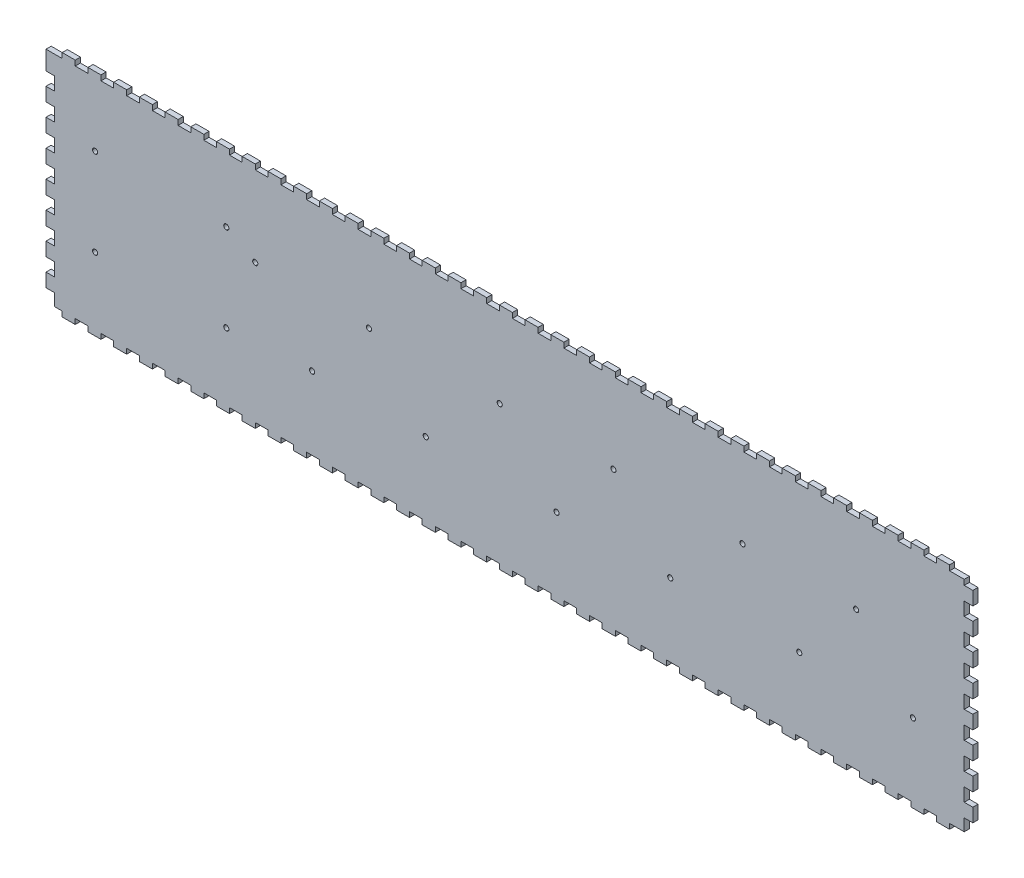
SolidWorks part; units mm, degrees
material "Perspex (TM) GS Acrylic Cast Sheet"
ref_plane "Front Plane" through (0, 0, 0) normal (0, 0, 1) x (1, 0, 0)
ref_plane "Top Plane" through (0, 0, 0) normal (0, 1, 0) x (1, 0, 0)
ref_plane "Right Plane" through (0, 0, 0) normal (1, 0, 0) x (0, 0, -1)
sketch "Sketch1" plane through (0, 0, 0) normal (0, 0, 1) x (1, 0, 0)
  line L0 (533.3602, 7.7159) -> (533.3602, 0.71)
  line L1 (9.4185, 0.71) -> (9.4185, -2.29)
  line L2 (9.4185, -2.29) -> (16.9869, -2.29)
  line L3 (16.9869, 0.71) -> (16.9869, -2.29)
  line L4 (16.9869, 0.71) -> (24.3553, 0.71)
  line L5 (24.3553, 0.71) -> (24.3553, -2.29)
  line L6 (24.3553, -2.29) -> (31.9238, -2.29)
  line L7 (31.9238, 0.71) -> (31.9238, -2.29)
  line L8 (31.9238, 0.71) -> (39.2923, 0.71)
  line L9 (39.2923, 0.71) -> (39.2923, -2.29)
  line L10 (39.2923, -2.29) -> (46.8607, -2.29)
  line L11 (46.8607, 0.71) -> (46.8607, -2.29)
  line L12 (46.8607, 0.71) -> (54.2292, 0.71)
  line L13 (54.2292, 0.71) -> (54.2292, -2.29)
  line L14 (54.2292, -2.29) -> (61.7976, -2.29)
  line L15 (61.7976, 0.71) -> (61.7976, -2.29)
  line L16 (61.7976, 0.71) -> (69.1661, 0.71)
  line L17 (69.1661, 0.71) -> (69.1661, -2.29)
  line L18 (69.1661, -2.29) -> (76.7345, -2.29)
  line L19 (76.7345, 0.71) -> (76.7345, -2.29)
  line L20 (76.7345, 0.71) -> (84.103, 0.71)
  line L21 (84.103, 0.71) -> (84.103, -2.29)
  line L22 (84.103, -2.29) -> (91.6715, -2.29)
  line L23 (91.6715, 0.71) -> (91.6715, -2.29)
  line L24 (91.6715, 0.71) -> (99.0399, 0.71)
  line L25 (99.0399, 0.71) -> (99.0399, -2.29)
  line L26 (99.0399, -2.29) -> (106.6084, -2.29)
  line L27 (106.6084, 0.71) -> (106.6084, -2.29)
  line L28 (106.6084, 0.71) -> (113.9769, 0.71)
  line L29 (113.9769, 0.71) -> (113.9769, -2.29)
  line L30 (113.9769, -2.29) -> (121.5454, -2.29)
  line L31 (121.5454, 0.71) -> (121.5454, -2.29)
  line L32 (121.5454, 0.71) -> (128.9139, 0.71)
  line L33 (128.9139, 0.71) -> (128.9139, -2.29)
  line L34 (128.9139, -2.29) -> (136.482, -2.29)
  line L35 (136.482, 0.71) -> (136.482, -2.29)
  line L36 (136.482, 0.71) -> (143.8505, 0.71)
  line L37 (143.8505, 0.71) -> (143.8505, -2.29)
  line L38 (143.8505, -2.29) -> (151.419, -2.29)
  line L39 (151.419, 0.71) -> (151.419, -2.29)
  line L40 (151.419, 0.71) -> (158.7874, 0.71)
  line L41 (158.7874, 0.71) -> (158.7874, -2.29)
  line L42 (158.7874, -2.29) -> (166.3559, -2.29)
  line L43 (166.3559, 0.71) -> (166.3559, -2.29)
  line L44 (166.3559, 0.71) -> (173.7244, 0.71)
  line L45 (173.7244, 0.71) -> (173.7244, -2.29)
  line L46 (173.7244, -2.29) -> (181.2929, -2.29)
  line L47 (181.2929, 0.71) -> (181.2929, -2.29)
  line L48 (181.2929, 0.71) -> (188.6613, 0.71)
  line L49 (188.6613, 0.71) -> (188.6613, -2.29)
  line L50 (188.6613, -2.29) -> (196.2298, -2.29)
  line L51 (196.2298, 0.71) -> (196.2298, -2.29)
  line L52 (196.2298, 0.71) -> (203.5983, 0.71)
  line L53 (203.5983, 0.71) -> (203.5983, -2.29)
  line L54 (203.5983, -2.29) -> (211.1665, -2.29)
  line L55 (211.1665, 0.71) -> (211.1665, -2.29)
  line L56 (211.1665, 0.71) -> (218.5349, 0.71)
  line L57 (218.5349, 0.71) -> (218.5349, -2.29)
  line L58 (218.5349, -2.29) -> (226.1034, -2.29)
  line L59 (226.1034, 0.71) -> (226.1034, -2.29)
  line L60 (226.1034, 0.71) -> (233.4719, 0.71)
  line L61 (233.4719, 0.71) -> (233.4719, -2.29)
  line L62 (233.4719, -2.29) -> (241.0404, -2.29)
  line L63 (241.0404, 0.71) -> (241.0404, -2.29)
  line L64 (241.0404, 0.71) -> (248.4089, 0.71)
  line L65 (248.4089, 0.71) -> (248.4089, -2.29)
  line L66 (248.4089, -2.29) -> (255.9774, -2.29)
  line L67 (255.9774, 0.71) -> (255.9774, -2.29)
  line L68 (255.9774, 0.71) -> (263.3458, 0.71)
  line L69 (263.3458, 0.71) -> (263.3458, -2.29)
  line L70 (263.3458, -2.29) -> (270.9143, -2.29)
  line L71 (270.9143, 0.71) -> (270.9143, -2.29)
  line L72 (270.9143, 0.71) -> (278.2828, 0.71)
  line L73 (278.2828, 0.71) -> (278.2828, -2.29)
  line L74 (278.2828, -2.29) -> (285.8513, -2.29)
  line L75 (285.8513, 0.71) -> (285.8513, -2.29)
  line L76 (285.8513, 0.71) -> (293.2197, 0.71)
  line L77 (293.2197, 0.71) -> (293.2197, -2.29)
  line L78 (293.2197, -2.29) -> (300.7879, -2.29)
  line L79 (300.7879, 0.71) -> (300.7879, -2.29)
  line L80 (300.7879, 0.71) -> (308.1564, 0.71)
  line L81 (308.1564, 0.71) -> (308.1564, -2.29)
  line L82 (308.1564, -2.29) -> (315.7248, -2.29)
  line L83 (315.7248, 0.71) -> (315.7248, -2.29)
  line L84 (315.7248, 0.71) -> (323.0933, 0.71)
  line L85 (323.0933, 0.71) -> (323.0933, -2.29)
  line L86 (323.0933, -2.29) -> (330.6618, -2.29)
  line L87 (330.6618, 0.71) -> (330.6618, -2.29)
  line L88 (330.6618, 0.71) -> (338.0303, 0.71)
  line L89 (338.0303, 0.71) -> (338.0303, -2.29)
  line L90 (338.0303, -2.29) -> (345.5988, -2.29)
  line L91 (345.5988, 0.71) -> (345.5988, -2.29)
  line L92 (345.5988, 0.71) -> (352.9673, 0.71)
  line L93 (352.9673, 0.71) -> (352.9673, -2.29)
  line L94 (352.9673, -2.29) -> (360.5358, -2.29)
  line L95 (360.5358, 0.71) -> (360.5358, -2.29)
  line L96 (360.5358, 0.71) -> (367.9042, 0.71)
  line L97 (367.9042, 0.71) -> (367.9042, -2.29)
  line L98 (367.9042, -2.29) -> (375.4727, -2.29)
  line L99 (375.4727, 0.71) -> (375.4727, -2.29)
  line L100 (375.4727, 0.71) -> (382.8408, 0.71)
  line L101 (382.8408, 0.71) -> (382.8408, -2.29)
  line L102 (382.8408, -2.29) -> (390.4093, -2.29)
  line L103 (390.4093, 0.71) -> (390.4093, -2.29)
  line L104 (390.4093, 0.71) -> (397.7778, 0.71)
  line L105 (397.7778, 0.71) -> (397.7778, -2.29)
  line L106 (397.7778, -2.29) -> (405.3463, -2.29)
  line L107 (405.3463, 0.71) -> (405.3463, -2.29)
  line L108 (405.3463, 0.71) -> (412.7147, 0.71)
  line L109 (412.7147, 0.71) -> (412.7147, -2.29)
  line L110 (412.7147, -2.29) -> (420.2832, -2.29)
  line L111 (420.2832, 0.71) -> (420.2832, -2.29)
  line L112 (420.2832, 0.71) -> (427.6517, 0.71)
  line L113 (427.6517, 0.71) -> (427.6517, -2.29)
  line L114 (427.6517, -2.29) -> (435.2202, -2.29)
  line L115 (435.2202, 0.71) -> (435.2202, -2.29)
  line L116 (435.2202, 0.71) -> (442.5887, 0.71)
  line L117 (442.5887, 0.71) -> (442.5887, -2.29)
  line L118 (442.5887, -2.29) -> (450.1572, -2.29)
  line L119 (450.1572, 0.71) -> (450.1572, -2.29)
  line L120 (450.1572, 0.71) -> (457.5257, 0.71)
  line L121 (457.5257, 0.71) -> (457.5257, -2.29)
  line L122 (457.5257, -2.29) -> (465.0938, -2.29)
  line L123 (465.0938, 0.71) -> (465.0938, -2.29)
  line L124 (465.0938, 0.71) -> (472.4623, 0.71)
  line L125 (472.4623, 0.71) -> (472.4623, -2.29)
  line L126 (472.4623, -2.29) -> (480.0308, -2.29)
  line L127 (480.0308, 0.71) -> (480.0308, -2.29)
  line L128 (480.0308, 0.71) -> (487.3268, 0.71)
  line L129 (487.3268, 0.71) -> (487.4716, -2.29)
  line L130 (487.4716, -2.29) -> (494.9677, -2.29)
  line L131 (494.9677, 0.71) -> (494.9677, -2.29)
  line L132 (494.9677, 0.71) -> (502.3362, 0.71)
  line L133 (502.3362, 0.71) -> (502.3362, -2.29)
  line L134 (502.3362, -2.29) -> (509.9047, -2.29)
  line L135 (509.9047, 0.71) -> (509.9047, -2.29)
  line L136 (509.9047, 0.71) -> (517.2731, 0.71)
  line L137 (517.2731, 0.71) -> (517.2731, -2.29)
  line L138 (517.2731, -2.29) -> (524.8416, -2.29)
  line L139 (524.8416, 0.71) -> (524.8416, -2.29)
  line L140 (524.8416, 0.71) -> (533.3602, 0.71)
  line L141 (0, 127.749) -> (9.4185, 127.749)
  line L142 (9.4185, 130.749) -> (9.4185, 127.749)
  line L143 (9.4185, 130.749) -> (16.9869, 130.749)
  line L144 (16.9869, 130.749) -> (16.9869, 127.749)
  line L145 (16.9869, 127.749) -> (24.3553, 127.749)
  line L146 (24.3553, 130.749) -> (24.3553, 127.749)
  line L147 (24.3553, 130.749) -> (31.9238, 130.749)
  line L148 (31.9238, 130.749) -> (31.9238, 127.749)
  line L149 (31.9238, 127.749) -> (39.2923, 127.749)
  line L150 (39.2923, 130.749) -> (39.2923, 127.749)
  line L151 (39.2923, 130.749) -> (46.8607, 130.749)
  line L152 (46.8607, 130.749) -> (46.8607, 127.749)
  line L153 (46.8607, 127.749) -> (54.2292, 127.749)
  line L154 (54.2292, 130.749) -> (54.2292, 127.749)
  line L155 (54.2292, 130.749) -> (61.7976, 130.749)
  line L156 (61.7976, 130.749) -> (61.7976, 127.749)
  line L157 (61.7976, 127.749) -> (69.1661, 127.749)
  line L158 (69.1661, 130.749) -> (69.1661, 127.749)
  line L159 (69.1661, 130.749) -> (76.7345, 130.749)
  line L160 (76.7345, 130.749) -> (76.7345, 127.749)
  line L161 (76.7345, 127.749) -> (84.103, 127.749)
  line L162 (84.103, 130.749) -> (84.103, 127.749)
  line L163 (84.103, 130.749) -> (91.6715, 130.749)
  line L164 (91.6715, 130.749) -> (91.6715, 127.749)
  line L165 (91.6715, 127.749) -> (99.0399, 127.749)
  line L166 (99.0399, 130.749) -> (99.0399, 127.749)
  line L167 (99.0399, 130.749) -> (106.6084, 130.749)
  line L168 (106.6084, 130.749) -> (106.6084, 127.749)
  line L169 (106.6084, 127.749) -> (113.9769, 127.749)
  line L170 (113.9769, 130.749) -> (113.9769, 127.749)
  line L171 (113.9769, 130.749) -> (121.5454, 130.749)
  line L172 (121.5454, 130.749) -> (121.5454, 127.749)
  line L173 (121.5454, 127.749) -> (128.9139, 127.749)
  line L174 (128.9139, 130.749) -> (128.9139, 127.749)
  line L175 (128.9139, 130.749) -> (136.482, 130.749)
  line L176 (136.482, 130.749) -> (136.482, 127.749)
  line L177 (136.482, 127.749) -> (143.8505, 127.749)
  line L178 (143.8505, 130.749) -> (143.8505, 127.749)
  line L179 (143.8505, 130.749) -> (151.419, 130.749)
  line L180 (151.419, 130.749) -> (151.419, 127.749)
  line L181 (151.419, 127.749) -> (158.7874, 127.749)
  line L182 (158.7874, 130.749) -> (158.7874, 127.749)
  line L183 (158.7874, 130.749) -> (166.3559, 130.749)
  line L184 (166.3559, 130.749) -> (166.3559, 127.749)
  line L185 (166.3559, 127.749) -> (173.7244, 127.749)
  line L186 (173.7244, 130.749) -> (173.7244, 127.749)
  line L187 (173.7244, 130.749) -> (181.2929, 130.749)
  line L188 (181.2929, 130.749) -> (181.2929, 127.749)
  line L189 (181.2929, 127.749) -> (188.6613, 127.749)
  line L190 (188.6613, 130.749) -> (188.6613, 127.749)
  line L191 (188.6613, 130.749) -> (196.2298, 130.749)
  line L192 (196.2298, 130.749) -> (196.2298, 127.749)
  line L193 (196.2298, 127.749) -> (203.5983, 127.749)
  line L194 (203.5983, 130.749) -> (203.5983, 127.749)
  line L195 (203.5983, 130.749) -> (211.1665, 130.749)
  line L196 (211.1665, 130.749) -> (211.1665, 127.749)
  line L197 (211.1665, 127.749) -> (218.5349, 127.749)
  line L198 (218.5349, 130.749) -> (218.5349, 127.749)
  line L199 (218.5349, 130.749) -> (226.1034, 130.749)
  line L200 (226.1034, 130.749) -> (226.1034, 127.749)
  line L201 (226.1034, 127.749) -> (233.4719, 127.749)
  line L202 (233.4719, 130.749) -> (233.4719, 127.749)
  line L203 (233.4719, 130.749) -> (241.0404, 130.749)
  line L204 (241.0404, 130.749) -> (241.0404, 127.749)
  line L205 (241.0404, 127.749) -> (248.4089, 127.749)
  line L206 (248.4089, 130.749) -> (248.4089, 127.749)
  line L207 (248.4089, 130.749) -> (255.9774, 130.749)
  line L208 (255.9774, 130.749) -> (255.9774, 127.749)
  line L209 (255.9774, 127.749) -> (263.3458, 127.749)
  line L210 (263.3458, 130.749) -> (263.3458, 127.749)
  line L211 (263.3458, 130.749) -> (270.9143, 130.749)
  line L212 (270.9143, 130.749) -> (270.9143, 127.749)
  line L213 (270.9143, 127.749) -> (278.2828, 127.749)
  line L214 (278.2828, 130.749) -> (278.2828, 127.749)
  line L215 (278.2828, 130.749) -> (285.8513, 130.749)
  line L216 (285.8513, 130.749) -> (285.8513, 127.749)
  line L217 (285.8513, 127.749) -> (293.2197, 127.749)
  line L218 (293.2197, 130.749) -> (293.2197, 127.749)
  line L219 (293.2197, 130.749) -> (300.7879, 130.749)
  line L220 (300.7879, 130.749) -> (300.7879, 127.749)
  line L221 (300.7879, 127.749) -> (308.1564, 127.749)
  line L222 (308.1564, 130.749) -> (308.1564, 127.749)
  line L223 (308.1564, 130.749) -> (315.7248, 130.749)
  line L224 (315.7248, 130.749) -> (315.7248, 127.749)
  line L225 (315.7248, 127.749) -> (323.0933, 127.749)
  line L226 (323.0933, 130.749) -> (323.0933, 127.749)
  line L227 (323.0933, 130.749) -> (330.6618, 130.749)
  line L228 (330.6618, 130.749) -> (330.6618, 127.749)
  line L229 (330.6618, 127.749) -> (338.0303, 127.749)
  line L230 (338.0303, 130.749) -> (338.0303, 127.749)
  line L231 (338.0303, 130.749) -> (345.5988, 130.749)
  line L232 (345.5988, 130.749) -> (345.5988, 127.749)
  line L233 (345.5988, 127.749) -> (352.9673, 127.749)
  line L234 (352.9673, 130.749) -> (352.9673, 127.749)
  line L235 (352.9673, 130.749) -> (360.5358, 130.749)
  line L236 (360.5358, 130.749) -> (360.5358, 127.749)
  line L237 (360.5358, 127.749) -> (367.9042, 127.749)
  line L238 (367.9042, 130.749) -> (367.9042, 127.749)
  line L239 (367.9042, 130.749) -> (375.4727, 130.749)
  line L240 (375.4727, 130.749) -> (375.4727, 127.749)
  line L241 (375.4727, 127.749) -> (382.8408, 127.749)
  line L242 (382.8408, 130.749) -> (382.8408, 127.749)
  line L243 (382.8408, 130.749) -> (390.4093, 130.749)
  line L244 (390.4093, 130.749) -> (390.4093, 127.749)
  line L245 (390.4093, 127.749) -> (397.7778, 127.749)
  line L246 (397.7778, 130.749) -> (397.7778, 127.749)
  line L247 (397.7778, 130.749) -> (405.3463, 130.749)
  line L248 (405.3463, 130.749) -> (405.3463, 127.749)
  line L249 (405.3463, 127.749) -> (412.7147, 127.749)
  line L250 (412.7147, 130.749) -> (412.7147, 127.749)
  line L251 (412.7147, 130.749) -> (420.2832, 130.749)
  line L252 (420.2832, 130.749) -> (420.2832, 127.749)
  line L253 (420.2832, 127.749) -> (427.6517, 127.749)
  line L254 (427.6517, 130.749) -> (427.6517, 127.749)
  line L255 (427.6517, 130.749) -> (435.2202, 130.749)
  line L256 (435.2202, 130.749) -> (435.2202, 127.749)
  line L257 (435.2202, 127.749) -> (442.5887, 127.749)
  line L258 (442.5887, 130.749) -> (442.5887, 127.749)
  line L259 (442.5887, 130.749) -> (450.1572, 130.749)
  line L260 (450.1572, 130.749) -> (450.1572, 127.749)
  line L261 (450.1572, 127.749) -> (457.5257, 127.749)
  line L262 (457.5257, 130.749) -> (457.5257, 127.749)
  line L263 (457.5257, 130.749) -> (465.0938, 130.749)
  line L264 (465.0938, 130.749) -> (465.0938, 127.749)
  line L265 (465.0938, 127.749) -> (472.4623, 127.749)
  line L266 (472.4623, 130.749) -> (472.4623, 127.749)
  line L267 (472.4623, 130.749) -> (480.0308, 130.749)
  line L268 (480.0308, 130.749) -> (480.0308, 127.749)
  line L269 (480.0308, 127.749) -> (487.3992, 127.749)
  line L270 (487.3992, 130.749) -> (487.3992, 127.749)
  line L271 (487.3992, 130.749) -> (494.9677, 130.749)
  line L272 (494.9677, 130.749) -> (494.9677, 127.749)
  line L273 (494.9677, 127.749) -> (502.3362, 127.749)
  line L274 (502.3362, 130.749) -> (502.3362, 127.749)
  line L275 (502.3362, 130.749) -> (509.9047, 130.749)
  line L276 (509.9047, 130.749) -> (509.9047, 127.749)
  line L277 (509.9047, 127.749) -> (517.2731, 127.749)
  line L278 (517.2731, 130.749) -> (517.2731, 127.749)
  line L279 (517.2731, 130.749) -> (524.8416, 130.749)
  line L280 (524.8416, 130.749) -> (524.8416, 127.749)
  line L281 (524.8416, 127.749) -> (533.3602, 127.749)
  line L282 (0, 127.749) -> (0, 116.7784)
  line L283 (5, 7.7159) -> (0, 7.7159)
  line L284 (0, 7.7159) -> (0, 15.6061)
  line L285 (5, 15.6061) -> (0, 15.6061)
  line L286 (5, 15.6061) -> (5, 23.2963)
  line L287 (5, 23.2963) -> (0, 23.2963)
  line L288 (0, 23.2963) -> (0, 31.1864)
  line L289 (5, 31.1864) -> (0, 31.1864)
  line L290 (5, 31.1864) -> (5, 38.8766)
  line L291 (5, 38.8766) -> (0, 38.8766)
  line L292 (0, 38.8766) -> (0, 46.7668)
  line L293 (5, 46.7668) -> (0, 46.7668)
  line L294 (5, 46.7668) -> (5, 54.457)
  line L295 (5, 54.457) -> (0, 54.457)
  line L296 (0, 54.457) -> (0, 62.3472)
  line L297 (5, 62.3472) -> (0, 62.3472)
  line L298 (5, 62.3472) -> (5, 70.0374)
  line L299 (5, 70.0374) -> (0, 70.0374)
  line L300 (0, 70.0374) -> (0, 77.9275)
  line L301 (5, 77.9275) -> (0, 77.9275)
  line L302 (5, 77.9275) -> (5, 85.6177)
  line L303 (5, 85.6177) -> (0, 85.6177)
  line L304 (0, 85.6177) -> (0, 93.5079)
  line L305 (5, 93.5079) -> (0, 93.5079)
  line L306 (5, 93.5079) -> (5, 101.1981)
  line L307 (5, 101.1981) -> (0, 101.1981)
  line L308 (0, 101.1981) -> (0, 109.0883)
  line L309 (5, 109.0883) -> (0, 109.0883)
  line L310 (5, 109.0883) -> (5, 116.7784)
  line L311 (5, 116.7784) -> (0, 116.7784)
  line L312 (5, 7.7159) -> (5, 0.71)
  line L313 (533.3602, 127.749) -> (533.3602, 124.6693)
  line L314 (538.3599, 7.7159) -> (533.3602, 7.7159)
  line L315 (538.3599, 7.7159) -> (538.3599, 15.6059)
  line L316 (538.3599, 15.6059) -> (533.3602, 15.6059)
  line L317 (533.3602, 15.6059) -> (533.3602, 23.2959)
  line L318 (538.3599, 23.2959) -> (533.3602, 23.2959)
  line L319 (538.3599, 23.2959) -> (538.3599, 31.1859)
  line L320 (538.3599, 31.1859) -> (533.3602, 31.1859)
  line L321 (533.3602, 31.1859) -> (533.3602, 38.8758)
  line L322 (538.3599, 38.8758) -> (533.3602, 38.8758)
  line L323 (538.3599, 38.8758) -> (538.3599, 46.7658)
  line L324 (538.3599, 46.7658) -> (533.3602, 46.7658)
  line L325 (533.3602, 46.7658) -> (533.3602, 54.4558)
  line L326 (538.3599, 54.4558) -> (533.3602, 54.4558)
  line L327 (538.3599, 54.4558) -> (538.3599, 62.3458)
  line L328 (538.3599, 62.3458) -> (533.3602, 62.3458)
  line L329 (533.3602, 62.3458) -> (533.3602, 70.0358)
  line L330 (538.3599, 70.0358) -> (533.3602, 70.0358)
  line L331 (538.3599, 70.0358) -> (538.3599, 77.9257)
  line L332 (538.3599, 77.9257) -> (533.3602, 77.9257)
  line L333 (533.3602, 77.9257) -> (533.3602, 85.6157)
  line L334 (538.3599, 85.6157) -> (533.3602, 85.6157)
  line L335 (538.3599, 85.6157) -> (538.3599, 93.5057)
  line L336 (538.3599, 93.5057) -> (533.3602, 93.5057)
  line L337 (533.3602, 93.5057) -> (533.3602, 101.2068)
  line L338 (538.3599, 101.2068) -> (533.3602, 101.2068)
  line L339 (538.3599, 101.2068) -> (538.3599, 109.0943)
  line L340 (538.3599, 109.0943) -> (533.3602, 109.0943)
  line L341 (533.3602, 109.0943) -> (533.3602, 116.7819)
  line L342 (538.3594, 116.7819) -> (533.3602, 116.7819)
  line L343 (538.3594, 116.7819) -> (538.3594, 124.6693)
  line L344 (538.3594, 124.6693) -> (533.3602, 124.6693)
  line L345 (5, 0.71) -> (9.4185, 0.71)
  line L346 (0, 127.749) -> (0, -2.29) construction
  line L347 (0, -2.29) -> (9.4185, -2.29) construction
  spline S0 degree 3 poles (502.0997, 43.109) (502.0997, 42.2807) (502.7711, 41.609) (503.5998, 41.609) knots 0 0 0 0 1 1 1 1
  spline S1 degree 3 poles (503.5998, 41.609) (504.4277, 41.609) (505.0998, 42.2807) (505.0998, 43.109) knots 0 0 0 0 1 1 1 1
  spline S2 degree 3 poles (505.0998, 43.109) (505.0998, 43.9377) (504.4277, 44.609) (503.5998, 44.609) knots 0 0 0 0 1 1 1 1
  spline S3 degree 3 poles (503.5998, 44.609) (502.7711, 44.609) (502.0997, 43.9377) (502.0997, 43.109) knots 0 0 0 0 1 1 1 1
  spline S4 degree 3 poles (469.0794, 81.209) (469.0794, 80.3807) (469.7507, 79.709) (470.5794, 79.709) knots 0 0 0 0 1 1 1 1
  spline S5 degree 3 poles (470.5794, 79.709) (471.4081, 79.709) (472.0794, 80.3807) (472.0794, 81.209) knots 0 0 0 0 1 1 1 1
  spline S6 degree 3 poles (472.0794, 81.209) (472.0794, 82.0377) (471.4081, 82.709) (470.5794, 82.709) knots 0 0 0 0 1 1 1 1
  spline S7 degree 3 poles (470.5794, 82.709) (469.7507, 82.709) (469.0794, 82.0377) (469.0794, 81.209) knots 0 0 0 0 1 1 1 1
  spline S8 degree 3 poles (436.0598, 43.109) (436.0598, 42.2807) (436.7311, 41.609) (437.5594, 41.609) knots 0 0 0 0 1 1 1 1
  spline S9 degree 3 poles (437.5594, 41.609) (438.3881, 41.609) (439.0594, 42.2807) (439.0594, 43.109) knots 0 0 0 0 1 1 1 1
  spline S10 degree 3 poles (439.0594, 43.109) (439.0594, 43.9377) (438.3881, 44.609) (437.5594, 44.609) knots 0 0 0 0 1 1 1 1
  spline S11 degree 3 poles (437.5594, 44.609) (436.7311, 44.609) (436.0598, 43.9377) (436.0598, 43.109) knots 0 0 0 0 1 1 1 1
  spline S12 degree 3 poles (403.0394, 81.209) (403.0394, 80.3807) (403.7108, 79.709) (404.5394, 79.709) knots 0 0 0 0 1 1 1 1
  spline S13 degree 3 poles (404.5394, 79.709) (405.3681, 79.709) (406.0394, 80.3807) (406.0394, 81.209) knots 0 0 0 0 1 1 1 1
  spline S14 degree 3 poles (406.0394, 81.209) (406.0394, 82.0377) (405.3681, 82.709) (404.5394, 82.709) knots 0 0 0 0 1 1 1 1
  spline S15 degree 3 poles (404.5394, 82.709) (403.7108, 82.709) (403.0394, 82.0377) (403.0394, 81.209) knots 0 0 0 0 1 1 1 1
  spline S16 degree 3 poles (361.0998, 43.109) (361.0998, 42.2807) (361.7712, 41.609) (362.5998, 41.609) knots 0 0 0 0 1 1 1 1
  spline S17 degree 3 poles (362.5998, 41.609) (363.4278, 41.609) (364.0998, 42.2807) (364.0998, 43.109) knots 0 0 0 0 1 1 1 1
  spline S18 degree 3 poles (364.0998, 43.109) (364.0998, 43.9377) (363.4278, 44.609) (362.5998, 44.609) knots 0 0 0 0 1 1 1 1
  spline S19 degree 3 poles (362.5998, 44.609) (361.7712, 44.609) (361.0998, 43.9377) (361.0998, 43.109) knots 0 0 0 0 1 1 1 1
  spline S20 degree 3 poles (328.0795, 81.209) (328.0795, 80.3807) (328.7508, 79.709) (329.5795, 79.709) knots 0 0 0 0 1 1 1 1
  spline S21 degree 3 poles (329.5795, 79.709) (330.4082, 79.709) (331.0795, 80.3807) (331.0795, 81.209) knots 0 0 0 0 1 1 1 1
  spline S22 degree 3 poles (331.0795, 81.209) (331.0795, 82.0377) (330.4082, 82.709) (329.5795, 82.709) knots 0 0 0 0 1 1 1 1
  spline S23 degree 3 poles (329.5795, 82.709) (328.7508, 82.709) (328.0795, 82.0377) (328.0795, 81.209) knots 0 0 0 0 1 1 1 1
  spline S24 degree 3 poles (295.0595, 43.109) (295.0595, 42.2807) (295.7312, 41.609) (296.5595, 41.609) knots 0 0 0 0 1 1 1 1
  spline S25 degree 3 poles (296.5595, 41.609) (297.3882, 41.609) (298.0595, 42.2807) (298.0595, 43.109) knots 0 0 0 0 1 1 1 1
  spline S26 degree 3 poles (298.0595, 43.109) (298.0595, 43.9377) (297.3882, 44.609) (296.5595, 44.609) knots 0 0 0 0 1 1 1 1
  spline S27 degree 3 poles (296.5595, 44.609) (295.7312, 44.609) (295.0595, 43.9377) (295.0595, 43.109) knots 0 0 0 0 1 1 1 1
  spline S28 degree 3 poles (262.0394, 81.209) (262.0394, 80.3807) (262.7108, 79.709) (263.5394, 79.709) knots 0 0 0 0 1 1 1 1
  spline S29 degree 3 poles (263.5394, 79.709) (264.368, 79.709) (265.0394, 80.3807) (265.0394, 81.209) knots 0 0 0 0 1 1 1 1
  spline S30 degree 3 poles (265.0394, 81.209) (265.0394, 82.0377) (264.368, 82.709) (263.5394, 82.709) knots 0 0 0 0 1 1 1 1
  spline S31 degree 3 poles (263.5394, 82.709) (262.7108, 82.709) (262.0394, 82.0377) (262.0394, 81.209) knots 0 0 0 0 1 1 1 1
  spline S32 degree 3 poles (28.5394, 89.1794) (27.7108, 89.1794) (27.0394, 89.8508) (27.0394, 90.6791) knots 0 0 0 0 1 1 1 1
  spline S33 degree 3 poles (27.0394, 90.6791) (27.0394, 91.5078) (27.7108, 92.1791) (28.5394, 92.1791) knots 0 0 0 0 1 1 1 1
  spline S34 degree 3 poles (28.5394, 92.1791) (29.3681, 92.1791) (30.0394, 91.5078) (30.0394, 90.6791) knots 0 0 0 0 1 1 1 1
  spline S35 degree 3 poles (30.0394, 90.6791) (30.0394, 89.8508) (29.3681, 89.1794) (28.5394, 89.1794) knots 0 0 0 0 1 1 1 1
  spline S36 degree 3 poles (28.5394, 38.3783) (27.7108, 38.3783) (27.0394, 39.0486) (27.0394, 39.8776) knots 0 0 0 0 1 1 1 1
  spline S37 degree 3 poles (27.0394, 39.8776) (27.0394, 40.7067) (27.7108, 41.3805) (28.5394, 41.3805) knots 0 0 0 0 1 1 1 1
  spline S38 degree 3 poles (28.5394, 41.3805) (29.3681, 41.3805) (30.0394, 40.7067) (30.0394, 39.8776) knots 0 0 0 0 1 1 1 1
  spline S39 degree 3 poles (30.0394, 39.8776) (30.0394, 39.0486) (29.3681, 38.3783) (28.5394, 38.3783) knots 0 0 0 0 1 1 1 1
  spline S40 degree 3 poles (104.7395, 38.3783) (103.9108, 38.3783) (103.2395, 39.0486) (103.2395, 39.8776) knots 0 0 0 0 1 1 1 1
  spline S41 degree 3 poles (103.2395, 39.8776) (103.2395, 40.7067) (103.9108, 41.3805) (104.7395, 41.3805) knots 0 0 0 0 1 1 1 1
  spline S42 degree 3 poles (104.7395, 41.3805) (105.5681, 41.3805) (106.2395, 40.7067) (106.2395, 39.8776) knots 0 0 0 0 1 1 1 1
  spline S43 degree 3 poles (106.2395, 39.8776) (106.2395, 39.0486) (105.5681, 38.3783) (104.7395, 38.3783) knots 0 0 0 0 1 1 1 1
  spline S44 degree 3 poles (104.7395, 89.1794) (103.9108, 89.1794) (103.2395, 89.8508) (103.2395, 90.6791) knots 0 0 0 0 1 1 1 1
  spline S45 degree 3 poles (103.2395, 90.6791) (103.2395, 91.5078) (103.9108, 92.1791) (104.7395, 92.1791) knots 0 0 0 0 1 1 1 1
  spline S46 degree 3 poles (104.7395, 92.1791) (105.5681, 92.1791) (106.2395, 91.5078) (106.2395, 90.6791) knots 0 0 0 0 1 1 1 1
  spline S47 degree 3 poles (106.2395, 90.6791) (106.2395, 89.8508) (105.5681, 89.1794) (104.7395, 89.1794) knots 0 0 0 0 1 1 1 1
  spline S48 degree 3 poles (219.0998, 43.109) (219.0998, 42.2807) (219.7712, 41.609) (220.5998, 41.609) knots 0 0 0 0 1 1 1 1
  spline S49 degree 3 poles (220.5998, 41.609) (221.4278, 41.609) (222.0998, 42.2807) (222.0998, 43.109) knots 0 0 0 0 1 1 1 1
  spline S50 degree 3 poles (222.0998, 43.109) (222.0998, 43.9377) (221.4278, 44.609) (220.5998, 44.609) knots 0 0 0 0 1 1 1 1
  spline S51 degree 3 poles (220.5998, 44.609) (219.7712, 44.609) (219.0998, 43.9377) (219.0998, 43.109) knots 0 0 0 0 1 1 1 1
  spline S52 degree 3 poles (186.0795, 81.209) (186.0795, 80.3807) (186.7508, 79.709) (187.5795, 79.709) knots 0 0 0 0 1 1 1 1
  spline S53 degree 3 poles (187.5795, 79.709) (188.4082, 79.709) (189.0795, 80.3807) (189.0795, 81.209) knots 0 0 0 0 1 1 1 1
  spline S54 degree 3 poles (189.0795, 81.209) (189.0795, 82.0377) (188.4082, 82.709) (187.5795, 82.709) knots 0 0 0 0 1 1 1 1
  spline S55 degree 3 poles (187.5795, 82.709) (186.7508, 82.709) (186.0795, 82.0377) (186.0795, 81.209) knots 0 0 0 0 1 1 1 1
  spline S56 degree 3 poles (153.0595, 43.109) (153.0595, 42.2807) (153.7312, 41.609) (154.5595, 41.609) knots 0 0 0 0 1 1 1 1
  spline S57 degree 3 poles (154.5595, 41.609) (155.3882, 41.609) (156.0595, 42.2807) (156.0595, 43.109) knots 0 0 0 0 1 1 1 1
  spline S58 degree 3 poles (156.0595, 43.109) (156.0595, 43.9377) (155.3882, 44.609) (154.5595, 44.609) knots 0 0 0 0 1 1 1 1
  spline S59 degree 3 poles (154.5595, 44.609) (153.7312, 44.609) (153.0595, 43.9377) (153.0595, 43.109) knots 0 0 0 0 1 1 1 1
  spline S60 degree 3 poles (120.0394, 81.209) (120.0394, 80.3807) (120.7108, 79.709) (121.5394, 79.709) knots 0 0 0 0 1 1 1 1
  spline S61 degree 3 poles (121.5394, 79.709) (122.368, 79.709) (123.0394, 80.3807) (123.0394, 81.209) knots 0 0 0 0 1 1 1 1
  spline S62 degree 3 poles (123.0394, 81.209) (123.0394, 82.0377) (122.368, 82.709) (121.5394, 82.709) knots 0 0 0 0 1 1 1 1
  spline S63 degree 3 poles (121.5394, 82.709) (120.7108, 82.709) (120.0394, 82.0377) (120.0394, 81.209) knots 0 0 0 0 1 1 1 1
extrude "Boss-Extrude1" add sketch "Sketch1" along normal blind 3
